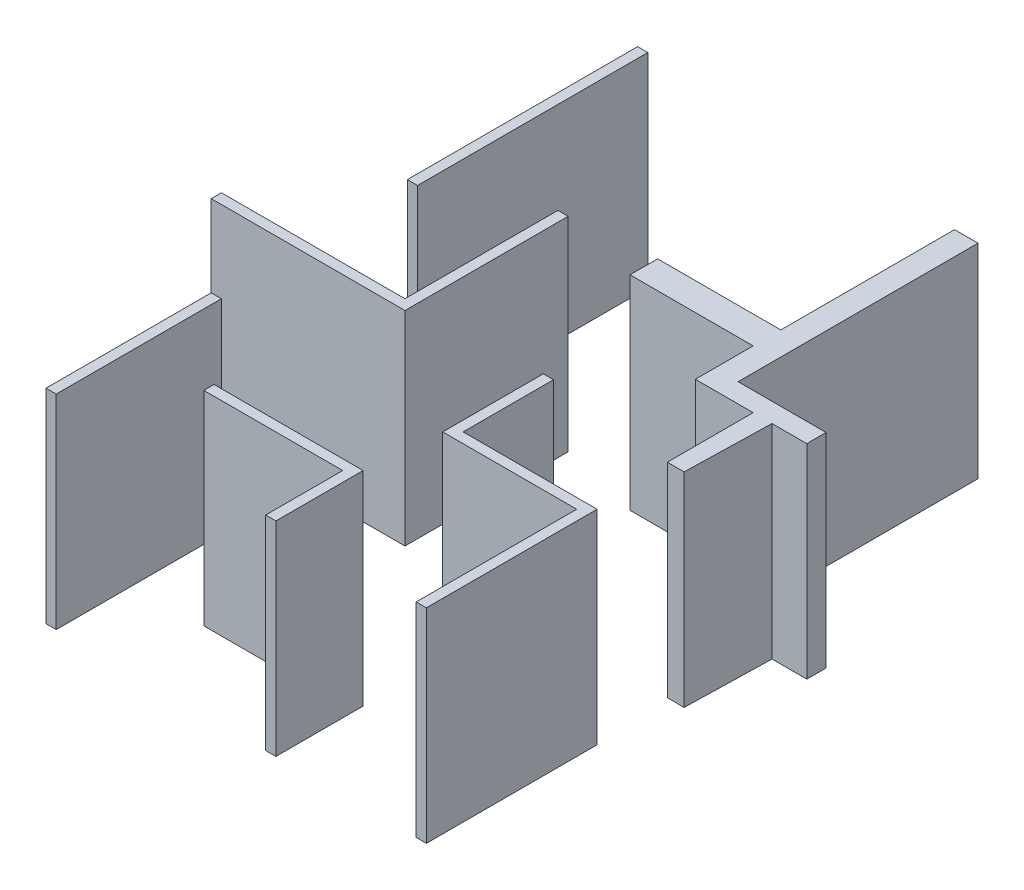
SolidWorks part; units mm, degrees
ref_plane "Front Plane" through (0, 0, 0) normal (0, 0, 1) x (1, 0, 0)
ref_plane "Top Plane" through (0, 0, 0) normal (0, 1, 0) x (1, 0, 0)
ref_plane "Right Plane" through (0, 0, 0) normal (1, 0, 0) x (0, 0, -1)
sketch "Sketch1" plane through (0, 0, 0) normal (0, 1, 0) x (1, 0, 0)
  line L18 (8462.0118, 4776.7457) -> (15769.1839, 4776.7457)
  line L19 (15769.1839, 4776.7457) -> (15769.1839, 500)
  line L20 (8462.0118, 4776.7457) -> (8462.0118, 4276.7457)
  line L21 (8462.0118, 4276.7457) -> (15269.1839, 4276.7457)
  line L22 (15269.1839, 4276.7457) -> (15269.1839, 500)
  line L54 (15269.1839, 500) -> (15769.1839, 500)
  point P0 (0, 0)
  dimension "D16" = 500
  dimension "D17" = 500
sketch "Sketch9" plane through (0, 0, 0) normal (0, 1, 0) x (1, 0, 0)
  line L13 (4500, 500) -> (4500, 8596.7551)
  line L14 (4500, 8596.7551) -> (5000, 8596.7551)
  line L15 (5000, 8596.7551) -> (5000, 500)
  line L56 (4500, 500) -> (5000, 500)
  point P0 (0, 0)
  dimension "D10" = 500
sketch "Sketch11" plane through (0, 0, 0) normal (0, 1, 0) x (1, 0, 0)
  line L36 (16579.4018, 13298.6717) -> (16579.4018, 8868.4685)
  line L37 (16579.4018, 8868.4685) -> (23146.6038, 8868.4685)
  line L38 (23146.6038, 8868.4685) -> (23146.6038, 500)
  line L40 (22646.6038, 500) -> (22646.6038, 8368.4685)
  line L41 (22646.6038, 8368.4685) -> (16079.4018, 8368.4685)
  line L42 (16079.4018, 8368.4685) -> (16079.4018, 13298.6717)
  line L43 (16079.4018, 13298.6717) -> (16579.4018, 13298.6717)
  line L55 (22646.6038, 500) -> (23146.6038, 500)
  point P0 (0, 0)
  dimension "D18" = 500
  dimension "D19" = 500
  dimension "D20" = 500
sketch "Sketch12" plane through (0, 0, 0) normal (0, 1, 0) x (1, 0, 0)
  line L28 (20037.0639, 29500) -> (20037.0639, 20983.6804)
  line L29 (20037.0639, 16794.6973) -> (22870.781, 16794.6973)
  line L30 (25500, 16794.6973) -> (25500, 17739.272)
  line L31 (25500, 17739.272) -> (21187.4624, 17739.272)
  line L32 (21187.4624, 17739.272) -> (21187.4624, 29500)
  line L33 (20037.0639, 20983.6804) -> (14000, 20983.6804)
  line L34 (14000, 20983.6804) -> (14000, 19628.4212)
  line L35 (14000, 19628.4212) -> (20037.0639, 19628.4212)
  line L44 (22870.781, 16794.6973) -> (22870.781, 12587.6548)
  line L45 (22870.781, 12587.6548) -> (23694.0368, 12587.6548)
  line L46 (23694.0368, 12587.6548) -> (23794.8281, 16794.6973)
  line L47 (20037.0639, 19628.4212) -> (20037.0639, 16794.6973)
  line L48 (23794.8281, 16794.6973) -> (25500, 16794.6973)
  line L52 (20037.0639, 29500) -> (21187.4624, 29500)
  point P0 (0, 0)
sketch "Sketch13" plane through (0, 0, 0) normal (0, 1, 0) x (1, 0, 0)
  line L0 (500, 13096.7551) -> (9500, 13096.7551)
  line L9 (9500, 13096.7551) -> (9500, 20596.7551)
  line L10 (9500, 20596.7551) -> (10000, 20596.7551)
  line L11 (10000, 20596.7551) -> (10000, 12596.7551)
  line L12 (10000, 12596.7551) -> (500, 12596.7551)
  line L53 (500, 13096.7551) -> (500, 12596.7551)
  point P0 (0, 0)
  dimension "D7" = 500
  dimension "D8" = 500
  dimension "D15" = 8000
sketch "Sketch14" plane through (0, 0, 0) normal (0, 1, 0) x (1, 0, 0)
  line L23 (4500, 18212.4546) -> (4500, 29500)
  line L24 (4500, 18212.4546) -> (5000, 18212.4546)
  line L25 (5000, 18212.4546) -> (5000, 29500)
  line L51 (4500, 29500) -> (5000, 29500)
  point P0 (0, 0)
  dimension "D13" = 500
extrude "Boss-Extrude5" add sketch "Sketch9" along normal blind 10000
extrude "Boss-Extrude6" add sketch "Sketch1" along normal blind 10000 separate body
extrude "Boss-Extrude7" add sketch "Sketch11" along normal blind 10000 separate body
extrude "Boss-Extrude8" add sketch "Sketch12" along normal blind 10000 separate body
extrude "Boss-Extrude9" add sketch "Sketch13" along normal blind 10000 separate body
extrude "Boss-Extrude10" add sketch "Sketch14" along normal blind 10000 separate body
